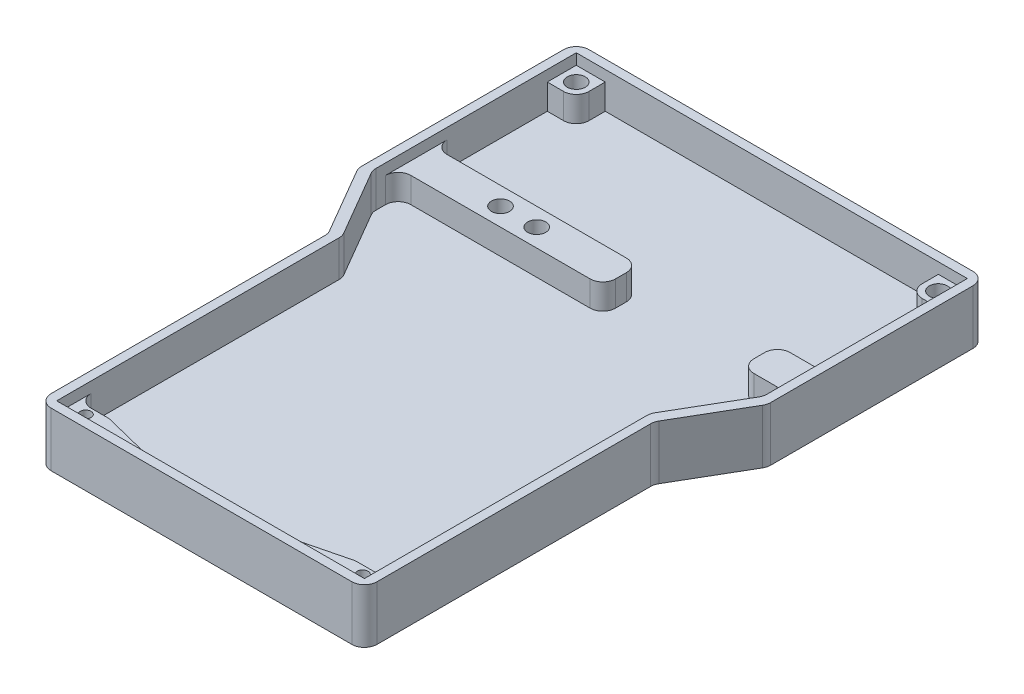
SolidWorks part; units mm, degrees
ref_plane "Front Plane" through (0, 0, 0) normal (0, 0, 1) x (1, 0, 0)
ref_plane "Top Plane" through (0, 0, 0) normal (0, 1, 0) x (1, 0, 0)
ref_plane "Right Plane" through (0, 0, 0) normal (1, 0, 0) x (0, 0, -1)
sketch "Sketch1" plane through (0, 0, 0) normal (0, 1, 0) x (1, 0, 0)
  line L0 (-57.5973, -8.4441) -> (-46.0973, -28.1941)
  line L1 (-46.0973, 51.8059) -> (43.9027, 51.8059)
  line L2 (-46.0973, 51.8059) -> (-46.0973, -108.1941)
  line L3 (-46.0973, -108.1941) -> (43.9027, -108.1941)
  line L4 (43.9027, 51.8059) -> (43.9027, -108.1941)
  line L5 (-57.5973, 51.8059) -> (55.4027, 51.8059)
  line L6 (-57.5973, 51.8059) -> (-57.5973, -8.4441)
  line L7 (-57.5973, -8.4441) -> (55.4027, -8.4441)
  line L8 (55.4027, 51.8059) -> (55.4027, -8.4441)
  line L9 (-57.5973, -8.4441) -> (-46.0973, -8.4441)
  line L10 (-46.0973, -8.4441) -> (-46.0973, -28.1941)
  line L11 (43.9027, -28.1941) -> (43.9027, -8.4441)
  line L12 (43.9027, -8.4441) -> (55.4027, -8.4441)
  line L13 (43.9027, -28.1941) -> (55.4027, -8.4441)
  point P12 (-1.0973, 51.8059)
  point P13 (-1.0973, 51.8059)
  dimension "D1" = 90
  dimension "D2" = 160
  dimension "D3" = 99.75
  dimension "D4" = 113
extrude "Boss-Extrude1" add sketch "Sketch1" along normal blind 5 contours L8 L5 L4 L7 | L2 L7 L4 L1 | L6 L7 L2 L5 | L7 L0 L2 | L7 L2 L3 L4 | L4 L13 L7
sketch "Sketch2" plane through (0, 5, 0) normal (0, 1, 0) x (1, 0, 0)
  line L0 (-46.0973, -108.1941) -> (43.9027, -108.1941)
  line L9 (43.9027, -108.1941) -> (43.9027, -28.1941)
  line L10 (43.9027, -28.1941) -> (55.4027, -8.4441)
  line L11 (55.4027, -8.4441) -> (55.4027, 51.8059)
  line L12 (55.4027, 51.8059) -> (-57.5973, 51.8059)
  line L13 (-57.5973, 51.8059) -> (-57.5973, -8.4441)
  line L14 (-57.5973, -8.4441) -> (-46.0973, -28.1941)
  line L15 (-46.0973, -28.1941) -> (-46.0973, -108.1941)
  line L16 (-43.5973, -105.6941) -> (41.4027, -105.6941)
  line L17 (41.4027, -105.6941) -> (41.4027, -26.7384)
  line L18 (41.4027, -26.7384) -> (52.9027, -6.9884)
  line L19 (52.9027, -6.9884) -> (52.9027, 49.3059)
  line L20 (52.9027, 49.3059) -> (-55.0973, 49.3059)
  line L21 (-55.0973, 49.3059) -> (-55.0973, -6.9884)
  line L22 (-55.0973, -6.9884) -> (-43.5973, -26.7384)
  line L23 (-43.5973, -26.7384) -> (-43.5973, -105.6941)
  line L24 (43.9027, -28.1941) -> (41.4027, -28.1941)
  line L25 (41.4027, -28.1941) -> (41.4027, -26.7384)
  line L26 (43.9027, -28.1941) -> (41.4027, -26.7384)
  line L27 (52.9027, -6.9884) -> (55.4027, -6.9884)
  line L28 (55.4027, -6.9884) -> (55.4027, -8.4441)
  line L29 (52.9027, -6.9884) -> (55.4027, -8.4441)
  line L30 (55.4027, -6.9884) -> (55.4027, -8.4441)
  line L31 (-55.0973, -6.9884) -> (-57.5973, -6.9884)
  line L32 (-57.5973, -6.9884) -> (-57.5973, -8.4441)
  line L33 (-57.5973, -8.4441) -> (-55.0973, -6.9884)
  line L34 (-43.5973, -26.7384) -> (-46.0973, -28.1941)
  line L35 (-46.0973, -28.1941) -> (-43.5973, -28.1941)
  line L36 (-43.5973, -28.1941) -> (-43.5973, -26.7384)
  line L37 (-57.5973, -6.9884) -> (-57.5973, -8.4441)
  dimension "D1" = 2.5
  dimension "D2" = 2.5
  dimension "D3" = 2.5
  dimension "D4" = 90
  dimension "D5" = 90
  dimension "D6" = 2.5
  dimension "D7" = 2.5
  dimension "D8" = 90
  dimension "D9" = 90
extrude "Boss-Extrude2" add sketch "Sketch2" along normal blind 10 contours L35 L15 L0 L9 L24 L17 L16 L23 | L29 L18 L26 L10 | L24 L26 L17 | L27 L29 L11 | L31 L21 L20 L19 L27 L11 L12 L13 | L34 L35 L23 | L34 L22 L33 L14 | L13 L33 L31
sketch "Sketch3" plane through (0, 5, 0) normal (0, 1, 0) x (1, 0, 0)
  line L0 (41.4027, -105.6941) -> (41.4027, 49.3059) construction
  line L1 (-43.5973, -105.6941) -> (41.4027, -105.6941)
  line L2 (-43.5973, -105.6941) -> (-43.5973, -99.6941)
  line L3 (-43.5973, -99.6941) -> (41.4027, -99.6941)
  line L4 (41.4027, -105.6941) -> (41.4027, -99.6941)
  line L5 (-35.0973, -99.6941) -> (-23.0973, -102.6941)
  line L6 (-23.0973, -102.6941) -> (20.9027, -102.6941)
  line L7 (20.9027, -102.6941) -> (32.9027, -99.6941)
  line L8 (-35.0973, -99.6941) -> (-35.0973, -105.6941)
  line L9 (-35.0973, -105.6941) -> (32.9027, -105.6941)
  line L10 (32.9027, -105.6941) -> (32.9027, -99.6941)
  line L11 (55.4027, 51.8059) -> (-57.5973, 51.8059) construction
  line L12 (-55.0973, 49.3059) -> (-47.0973, 49.3059)
  line L13 (-55.0973, 49.3059) -> (-55.0973, 41.3059)
  line L14 (-55.0973, 41.3059) -> (-47.0973, 41.3059)
  line L15 (-47.0973, 49.3059) -> (-47.0973, 41.3059)
  line L16 (52.9027, 49.3059) -> (44.9027, 49.3059)
  line L17 (52.9027, 49.3059) -> (52.9027, 41.3059)
  line L18 (52.9027, 41.3059) -> (44.9027, 41.3059)
  line L19 (44.9027, 49.3059) -> (44.9027, 41.3059)
  circle A0 centre (-39.3473, -101.9441) radius 1.5
  circle A1 centre (37.1527, -101.9441) radius 1.5
  circle A2 centre (-51.0973, 45.3059) radius 2.5
  circle A3 centre (48.9027, 45.3059) radius 2.5
  point P32 (-55.0973, 45.3059)
  point P33 (-51.0973, 41.3059)
  point P34 (48.9027, 41.3059)
  point P35 (44.9027, 45.3059)
  dimension "D4" = 3
  dimension "D7" = 3
  dimension "D17" = 5
  dimension "D18" = 5
  dimension "D1" = 6
  dimension "D2" = 4.25
  dimension "D3" = 3.75
  dimension "D5" = 76.5
  dimension "D6" = 4.25
  dimension "D8" = 12
  dimension "D9" = 12
  dimension "D10" = 3
  dimension "D11" = 8.5
  dimension "D12" = 8.5
  dimension "D13" = 8
  dimension "D14" = 8
  dimension "D15" = 8
  dimension "D16" = 8
  dimension "D19" = 6.5
extrude "Boss-Extrude3" add sketch "Sketch3" along normal blind 7
sketch "Sketch4" plane through (0, 5, 0) normal (0, 1, 0) x (1, 0, 0)
  line L0 (-43.5973, 49.3059) -> (-43.5973, -99.6941) construction
  line L1 (-43.5973, 10.1309) -> (1.4027, 10.1309)
  line L2 (-43.5973, 10.1309) -> (-43.5973, 0.1309)
  line L3 (-43.5973, 0.1309) -> (1.4027, 0.1309)
  line L4 (1.4027, 10.1309) -> (1.4027, 0.1309)
  line L5 (41.4027, 49.3059) -> (-43.5973, 49.3059) construction
  line L6 (41.4027, -99.6941) -> (41.4027, 49.3059) construction
  line L7 (1.4027, 10.1309) -> (-43.5973, 10.1309)
  line L8 (1.4027, 10.1309) -> (1.4027, 49.3059)
  line L9 (1.4027, 49.3059) -> (-43.5973, 49.3059)
  line L10 (-43.5973, 10.1309) -> (-43.5973, 49.3059)
  line L11 (39.6145, 10.1309) -> (41.4027, 10.1309)
  line L12 (39.6145, 10.1309) -> (39.6145, 0.1309)
  line L13 (39.6145, 0.1309) -> (41.4027, 0.1309)
  line L14 (41.4027, 10.1309) -> (41.4027, 0.1309)
  line L15 (-55.0973, 49.3059) -> (-55.0973, -6.9884) construction
  line L16 (-43.5973, 0.1309) -> (-55.0973, 0.1309)
  line L17 (-43.5973, 0.1309) -> (-43.5973, 10.1309)
  line L18 (-43.5973, 10.1309) -> (-55.0973, 10.1309)
  line L19 (-55.0973, 0.1309) -> (-55.0973, 10.1309)
  line L20 (52.9027, -6.9884) -> (52.9027, 49.3059) construction
  line L21 (41.4027, 10.1309) -> (52.9027, 10.1309)
  line L22 (41.4027, 10.1309) -> (41.4027, 0.1309)
  line L23 (41.4027, 0.1309) -> (52.9027, 0.1309)
  line L24 (52.9027, 10.1309) -> (52.9027, 0.1309)
  circle A0 centre (-31.8473, 5.1309) radius 2.5
  circle A1 centre (-21.8473, 5.1309) radius 2.5
  dimension "D3" = 5
  dimension "D4" = 5
  dimension "D1" = 11.75
  dimension "D2" = 21.75
  dimension "D5" = 10
  dimension "D6" = 5
  dimension "D7" = 5
  dimension "D8" = 44.175
  dimension "D9" = 45
extrude "Boss-Extrude4" add sketch "Sketch4" along normal up to surface (7 mm away)
fillet "Fillet1" radius 3.5 28 edges at (43.9027, 7.5, 108.1941) (-46.0973, 7.5, 108.1941) (52.9027, 8.5, -10.1309) (52.9027, 8.5, -0.1309) (-55.0973, 8.5, -10.1309) (-55.0973, 8.5, -0.1309) (41.4027, 8.5, 99.6941) (-43.5973, 8.5, 99.6941) (-35.0973, 8.5, 99.6941) (-23.0973, 8.5, 102.6941) (32.9027, 8.5, 99.6941) (20.9027, 8.5, 102.6941) (52.9027, 10, 6.9884) (41.4027, 10, 26.7384) (-43.5973, 10, 26.7384) (-55.0973, 10, 6.9884) (39.6145, 8.5, -10.1309) (39.6145, 8.5, -0.1309) (1.4027, 8.5, -10.1309) (1.4027, 8.5, -0.1309) (44.9027, 8.5, -41.3059) (-47.0973, 8.5, -41.3059) (43.9027, 7.5, 28.1941) (55.4027, 7.5, 8.4441) (55.4027, 7.5, -51.8059) (-57.5973, 7.5, -51.8059) (-57.5973, 7.5, 8.4441) (-46.0973, 7.5, 28.1941)
sketch "Sketch5" plane through (0, 5, 0) normal (0, 1, 0) x (1, 0, 0)
  circle A0 centre (-21.8473, 5.1309) radius 2.5
  circle A1 centre (-31.8473, 5.1309) radius 2.5593
  circle A2 centre (-39.3473, -101.9441) radius 1.5
  circle A3 centre (37.1527, -101.9441) radius 1.5
  circle A4 centre (-51.0973, 45.3059) radius 2.5
  circle A5 centre (48.9027, 45.3059) radius 2.5
extrude "Cut-Extrude1" cut sketch "Sketch5" against normal through all
